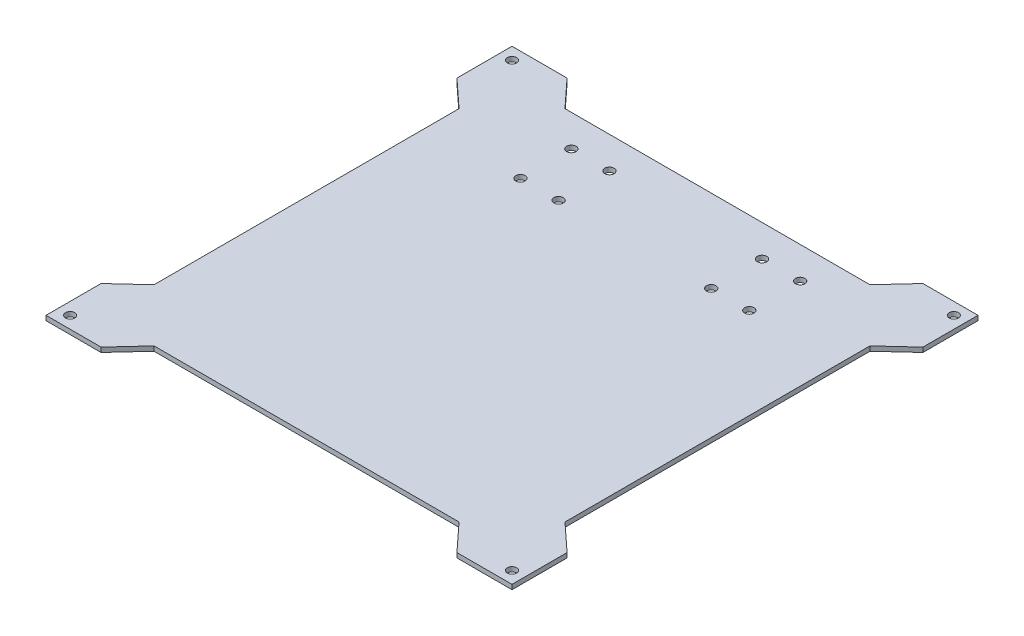
SolidWorks part; units mm, degrees
ref_plane "Front Plane" through (0, 0, 0) normal (0, 0, 1) x (1, 0, 0)
ref_plane "Top Plane" through (0, 0, 0) normal (0, 1, 0) x (1, 0, 0)
ref_plane "Right Plane" through (0, 0, 0) normal (1, 0, 0) x (0, 0, -1)
sketch "Sketch1" plane through (0, 0, 0) normal (0, 1, 0) x (1, 0, 0)
  line L0 (0, 0) -> (72, 0)
  line L1 (72, 0) -> (84, -13)
  line L2 (84, -13) -> (110, -13)
  line L3 (110, -13) -> (110, 13)
  line L4 (110, 13) -> (97, 25)
  line L5 (97, 25) -> (97, 97)
  line L6 (104.3, -7.3) -> (106.5, -7.3) construction
  line L7 (104.3, -9.5) -> (104.3, -7.3) construction
  line L8 (0, 0) -> (0, 97) construction
  line L9 (0, 97) -> (97, 97) construction
  line L10 (-97, 97) -> (-97, 25)
  line L11 (-97, 25) -> (-110, 13)
  line L12 (-110, 13) -> (-110, -13)
  line L13 (-110, -13) -> (-84, -13)
  line L14 (-84, -13) -> (-72, 0)
  line L15 (-72, 0) -> (0, 0)
  line L16 (0, 194) -> (-72, 194)
  line L17 (-72, 194) -> (-84, 207)
  line L18 (-84, 207) -> (-110, 207)
  line L19 (-110, 207) -> (-110, 181)
  line L20 (-110, 181) -> (-97, 169)
  line L21 (-97, 169) -> (-97, 97)
  line L22 (97, 97) -> (97, 169)
  line L23 (97, 169) -> (110, 181)
  line L24 (110, 181) -> (110, 207)
  line L25 (110, 207) -> (84, 207)
  line L26 (84, 207) -> (72, 194)
  line L27 (72, 194) -> (0, 194)
  circle A0 centre (104.3, -7.3) radius 2.2
  circle A1 centre (-104.3, -7.3) radius 2.2
  circle A2 centre (-104.3, 201.3) radius 2.2
  circle A3 centre (104.3, 201.3) radius 2.2
  point P4 (0, 0)
  point P39 (0, 97)
  dimension "D9" = 4.4
  dimension "D1" = 72
  dimension "D2" = 26
  dimension "D3" = 110
  dimension "D4" = 72
  dimension "D5" = 110
  dimension "D6" = 13
  dimension "D7" = 13
  dimension "D8" = 26
  dimension "D10" = 3.5
  dimension "D11" = 3.5
  dimension "D12" = 4
extrude "Boss-Extrude1" add sketch "Sketch1" along normal blind 2.2 contours L26 L27 L16 L17 L18 L19 L20 L21 L10 L11 L12 L13 L14 L15 L0 L1 L2 L3 L4 L5 L22 L23 L24 L25 A3 A2 A1 A0
sketch "Sketch2" plane through (0, 2.2, 0) normal (0, 1, 0) x (1, 0, 0)
  line L0 (-54.025, 179.025) -> (-54.025, 181.25) construction
  line L1 (-54.025, 179.025) -> (-56.25, 179.025) construction
  line L2 (-97, 169) -> (-97, 25) construction
  line L3 (72, 194) -> (-72, 194) construction
  line L4 (0, 194) -> (0, 170.2113) construction
  circle A0 centre (-54.025, 179.025) radius 2.225
  circle A1 centre (-36.025, 179.025) radius 2.225
  circle A2 centre (-54.025, 155.025) radius 2.225
  circle A3 centre (-36.025, 155.025) radius 2.225
  circle A4 centre (36.025, 155.025) radius 2.225
  circle A5 centre (54.025, 155.025) radius 2.225
  circle A6 centre (36.025, 179.025) radius 2.225
  circle A7 centre (54.025, 179.025) radius 2.225
  dimension "D3" = 4.45
  dimension "D1" = 18
  dimension "D2" = 24
  dimension "D4" = 40.75
  dimension "D5" = 12.75
extrude "Cut-Extrude1" cut sketch "Sketch2" against normal through all
